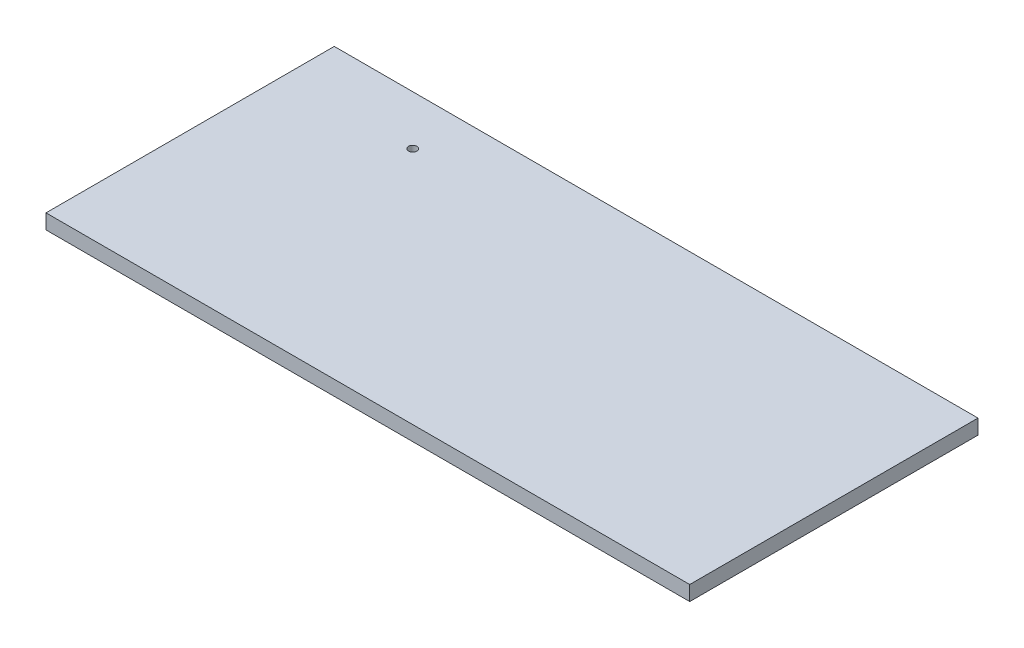
SolidWorks part; units mm, degrees
ref_plane "Front" through (0, 0, 0) normal (0, 0, 1) x (1, 0, 0)
ref_plane "Top" through (0, 0, 0) normal (0, 1, 0) x (1, 0, 0)
ref_plane "Right" through (0, 0, 0) normal (1, 0, 0) x (0, 0, -1)
sketch "Sketch1" plane through (0, 0, 0) normal (0, 1, 0) x (1, 0, 0)
  line L1 (0, 0) -> (130.41, 0)
  line L2 (0, 0) -> (0, -58.4)
  line L3 (0, -58.4) -> (130.41, -58.4)
  line L4 (130.41, 0) -> (130.41, -58.4)
  dimension "D1" = 58.4
  dimension "D2" = 130.41
extrude "Boss-Extrude1" add sketch "Sketch1" along normal blind 3
sketch "Sketch3" plane through (0, 3, 0) normal (0, 1, 0) x (1, 0, 0)
  line L1 (0, 0) -> (0, -58.4) construction
  line L2 (130.41, 0) -> (0, 0) construction
  circle A0 centre (25.89, -10) radius 0.85
  dimension "D1" = 1.7
  dimension "D2" = 10
  dimension "D3" = 25.89
extrude "Cut-Extrude1" cut sketch "Sketch3" against normal through all
